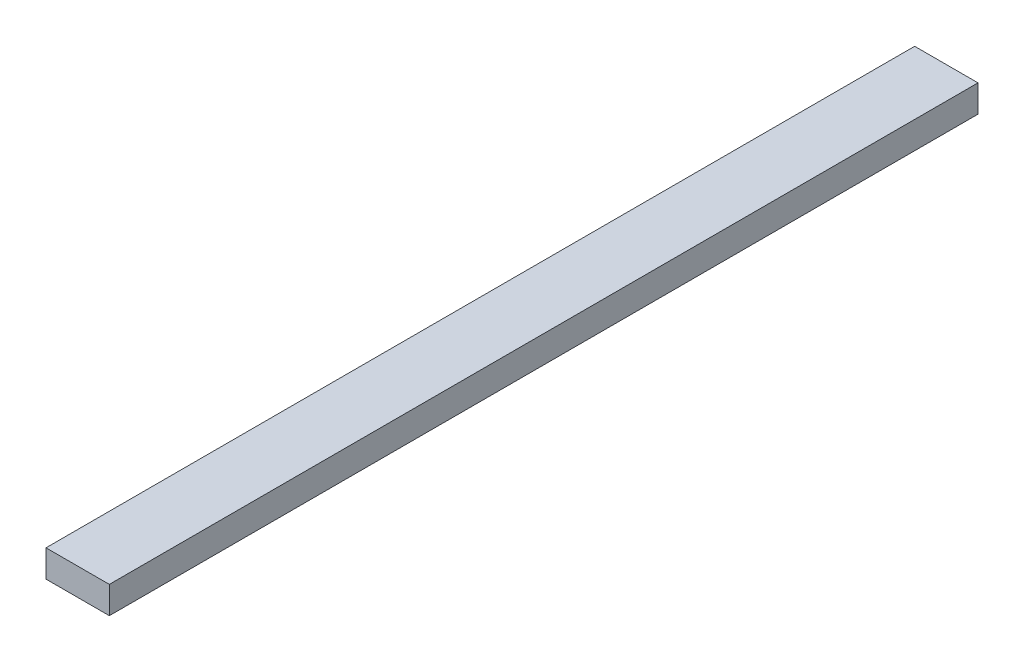
SolidWorks part; units mm, degrees
material "Pine"
ref_plane "Front Plane" through (0, 0, 0) normal (0, 0, 1) x (1, 0, 0)
ref_plane "Top Plane" through (0, 0, 0) normal (0, 1, 0) x (1, 0, 0)
ref_plane "Right Plane" through (0, 0, 0) normal (1, 0, 0) x (0, 0, -1)
sketch "Sketch1" plane through (0, 0, 0) normal (0, 0, 1) x (1, 0, 0)
  line L1 (0, 0) -> (88.9, 0)
  line L2 (0, 0) -> (0, 38.1)
  line L3 (0, 38.1) -> (88.9, 38.1)
  line L4 (88.9, 0) -> (88.9, 38.1)
  dimension "D1" = 88.9
  dimension "D2" = 38.1
extrude "Boss-Extrude1" add sketch "Sketch1" along normal blind 1219.2
sketch "Sketch2" plane through (0, 0, 0) normal (0, 0, -1) x (-1, 0, 0)
  line L1 (-88.9, 0) -> (-88.9, 38.1) construction
  line L2 (0, 38.1) -> (0, 0) construction
  line L3 (-44.45, 19.05) -> (-88.9, 19.05) construction
  line L4 (-44.45, 19.05) -> (0, 19.05) construction
  circle A0 centre (-66.675, 19.05) radius 0.8763
  circle A1 centre (-22.225, 19.05) radius 0.8763
  dimension "D1" = 1.7526
sketch "Sketch3" plane through (0, 0, 0) normal (0, -1, 0) x (1, 0, 0)
  line L0 (44.45, 1219.2) -> (44.45, 1174.75) construction
  line L1 (0, 1219.2) -> (88.9, 1219.2) construction
  line L2 (44.45, 1174.75) -> (44.45, 1130.3) construction
  line L3 (88.9, 609.6) -> (0, 609.6) construction
  line L4 (88.9, 1219.2) -> (88.9, 0) construction
  line L5 (0, 1219.2) -> (0, 0) construction
  line L6 (44.45, 609.6) -> (44.45, 654.05) construction
  line L7 (44.45, 609.6) -> (44.45, 565.15) construction
  circle A0 centre (44.45, 1196.975) radius 0.8763
  circle A1 centre (44.45, 1152.525) radius 0.8763
  circle A2 centre (44.45, 22.225) radius 0.8763
  circle A3 centre (44.45, 66.675) radius 0.8763
  circle A4 centre (44.45, 587.375) radius 0.8763
  circle A5 centre (44.45, 631.825) radius 0.8763
  dimension "D2" = 1.7526
  dimension "D4" = 1.7526
  dimension "D1" = 88.9
  dimension "D3" = 88.9
equation "\"length\"= 20"
equation "\"length\"= 22"
equation "\"length\"= 36"
equation "\"length\"= 26"
equation "\"length\"= 27"
equation "\"length\"= 28"
equation "\"length\"= 39"
equation "\"length\"= 96"
equation "\"length\"= 30"
equation "\"length\"= 32"
